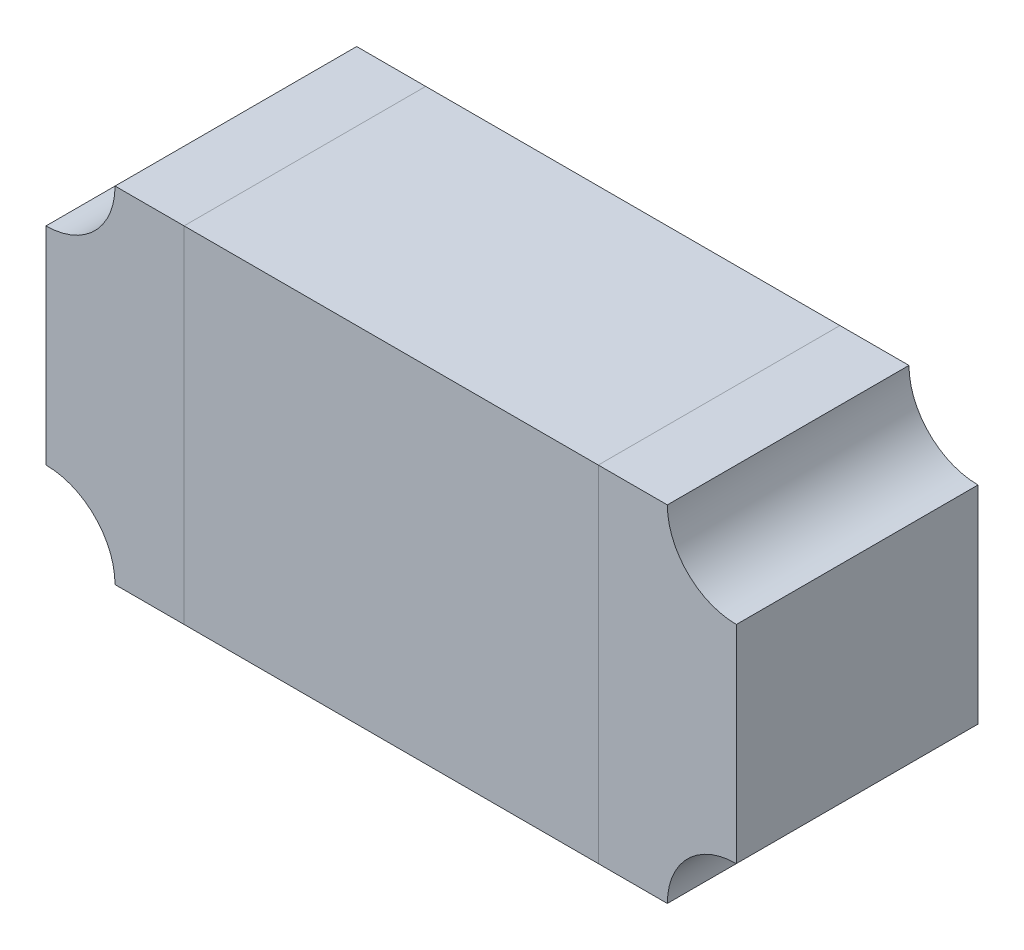
SolidWorks part; units mm, degrees
ref_plane "Front Plane" through (0, 0, 0) normal (0, 0, 1) x (1, 0, 0)
ref_plane "Top Plane" through (0, 0, 0) normal (0, 1, 0) x (1, 0, 0)
ref_plane "Right Plane" through (0, 0, 0) normal (1, 0, 0) x (0, 0, -1)
sketch "Sketch1" plane through (0, 0, 0) normal (0, 0, 1) x (1, 0, 0)
  line L1 (-0.3, -0.25) -> (0.3, -0.25)
  line L2 (-0.3, -0.25) -> (-0.3, 0.25)
  line L3 (-0.3, 0.25) -> (0.3, 0.25)
  line L4 (0.3, -0.25) -> (0.3, 0.25)
  line L5 (-0.3, -0.25) -> (0.3, 0.25) construction
  line L6 (-0.3, 0.25) -> (0.3, -0.25) construction
  point P0 (0, 0)
  dimension "D1" = 0.6
  dimension "D2" = 0.5
extrude "Boss-Extrude1" add sketch "Sketch1" along normal blind 0.35
sketch "Sketch2" plane through (0, 0, 0) normal (0, 0, 1) x (1, 0, 0)
  line L0 (-0.3, -0.25) -> (-0.4, -0.25)
  line L1 (-0.5, -0.15) -> (-0.5, 0.15)
  line L2 (-0.4, 0.25) -> (-0.3, 0.25)
  line L3 (-0.5, -0.15) -> (-0.5, -0.25) construction
  line L4 (-0.5, -0.25) -> (-0.4, -0.25) construction
  line L5 (-0.3, 0.25) -> (-0.3, -0.25) construction
  line L6 (-0.4, 0.25) -> (-0.5, 0.25) construction
  line L7 (-0.5, 0.25) -> (-0.5, 0.15) construction
  line L8 (-0.3, 0.25) -> (-0.3, -0.25)
  line L9 (0, 0.25) -> (0, -0.4243) construction
  line L10 (0.3, 0.25) -> (-0.3, 0.25) construction
  line L11 (0.5, 0.25) -> (0.5, 0.15) construction
  line L12 (0.4, 0.25) -> (0.5, 0.25) construction
  line L13 (0.5, -0.25) -> (0.4, -0.25) construction
  line L14 (0.5, -0.15) -> (0.5, -0.25) construction
  line L15 (0.3, 0.25) -> (0.3, -0.25)
  line L16 (0.4, 0.25) -> (0.3, 0.25)
  line L17 (0.5, -0.15) -> (0.5, 0.15)
  line L18 (0.3, -0.25) -> (0.4, -0.25)
  arc A0 (-0.5, -0.15) -> (-0.4, -0.25) centre (-0.5, -0.25) cw
  arc A1 (-0.5, 0.15) -> (-0.4, 0.25) centre (-0.5, 0.25) ccw
  arc A2 (0.5, 0.15) -> (0.4, 0.25) centre (0.5, 0.25) cw
  arc A3 (0.5, -0.15) -> (0.4, -0.25) centre (0.5, -0.25) ccw
  dimension "D1" = 0.2
  dimension "D2" = 0.1
extrude "Boss-Extrude2" add sketch "Sketch2" along normal up to surface (0.35 mm away) separate body up to face at (0, 0, 0.35)
